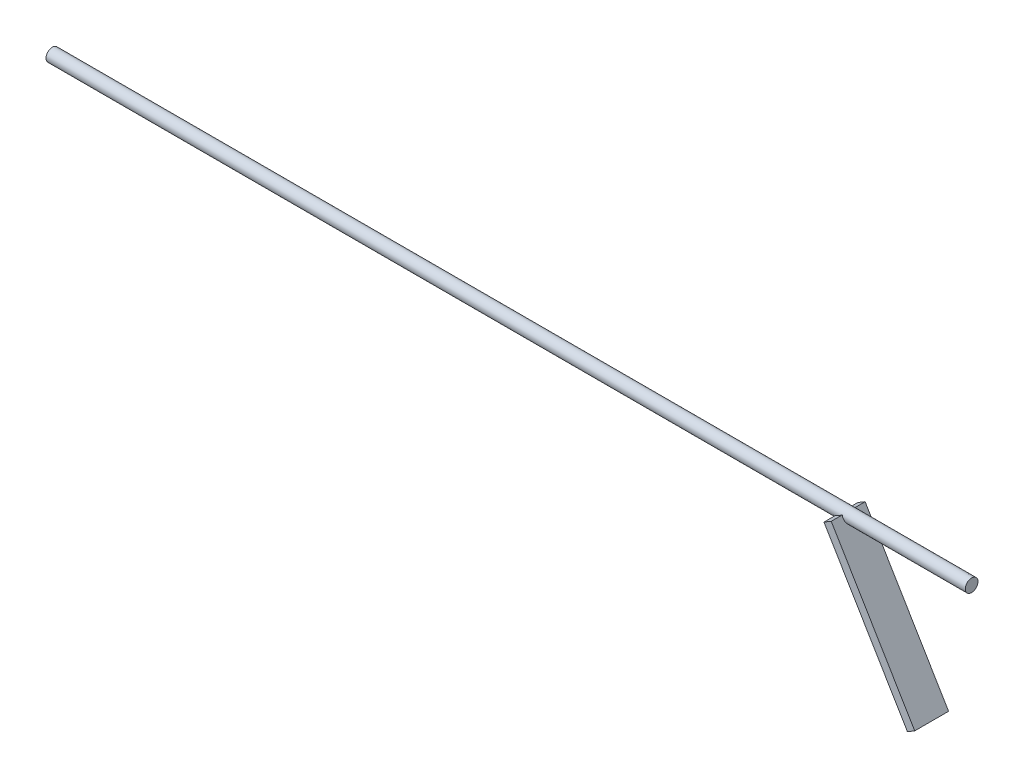
SolidWorks part; units mm, degrees
material "Plain Carbon Steel"
ref_plane "Front Plane" through (0, 0, 0) normal (0, 0, 1) x (1, 0, 0)
ref_plane "Top Plane" through (0, 0, 0) normal (0, 1, 0) x (1, 0, 0)
ref_plane "Right Plane" through (0, 0, 0) normal (1, 0, 0) x (0, 0, -1)
sketch "Sketch1" plane through (0, 0, 0) normal (1, 0, 0) x (0, 0, -1)
  circle A0 centre (0, 0) radius 1.5
  dimension "D1" = 3
extrude "Boss-Extrude1" add sketch "Sketch1" along normal blind 217 from offset 197
sketch "Sketch2" plane through (0, 0, 0) normal (0, 0, 1) x (1, 0, 0)
  line L0 (-10.8586, -0.5126) -> (-9.1414, 0.5126)
  line L1 (-9.1414, 0.5126) -> (10.5586, -32.4874)
  line L2 (10.5586, -32.4874) -> (8.8414, -33.5126)
  line L3 (8.8414, -33.5126) -> (-10.8586, -0.5126)
  dimension "D1" = 10.8586
  dimension "D2" = 0.5126
  dimension "D3" = 1.7173
  dimension "D4" = 1.0252
  dimension "D5" = 19.7
  dimension "D6" = 33
  dimension "D7" = 1.7173
  dimension "D8" = 1.0252
extrude "Boss-Extrude2" add sketch "Sketch2" along normal blind 8 from offset 4
